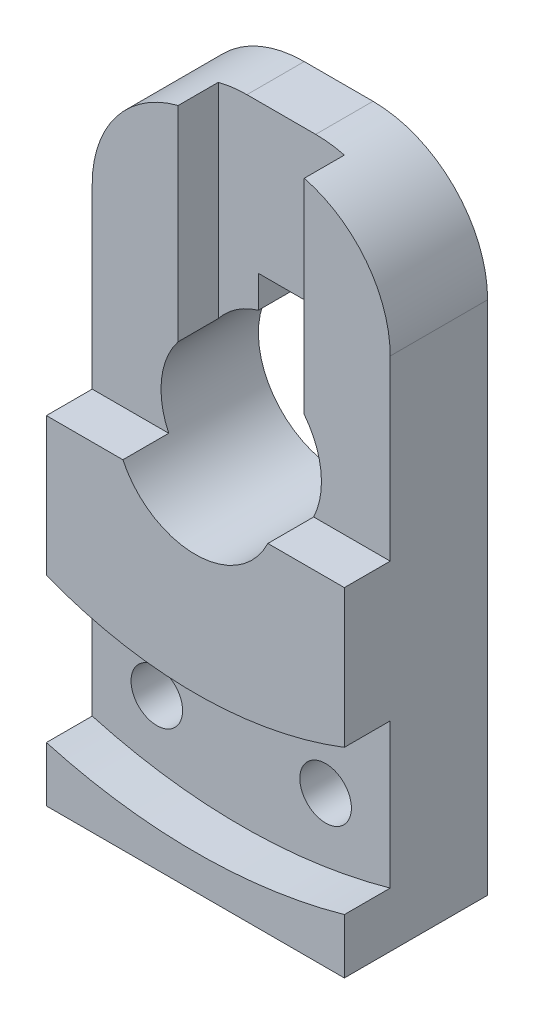
SolidWorks part; units mm, degrees
ref_plane "Front Plane" through (0, 0, 0) normal (1, 0, 0) x (0, 1, 0)
ref_plane "Top Plane" through (0, 0, 0) normal (0, 0, 1) x (0, 1, 0)
ref_plane "Right Plane" through (0, 0, 0) normal (0, 1, 0) x (-1, 0, 0)
sketch "Sketch1" plane through (0, 0, 0) normal (0, 0, 1) x (0, 1, 0)
  line L0 (0, 0) -> (0, 26)
  line L1 (0, 26) -> (90, 26)
  line L2 (110, 6) -> (110, -6)
  line L3 (90, -26) -> (0, -26)
  line L4 (0, -26) -> (0, 26)
  line L5 (110, 0) -> (102, 0) construction
  line L6 (78.4164, 4) -> (84, 4)
  line L8 (78.4164, -4) -> (84, -4)
  line L9 (84, 4) -> (84, -4)
  line L10 (102, 0) -> (17, 0) construction
  arc A0 (90, 26) -> (110, 6) centre (90, 6) cw
  arc A1 (110, -6) -> (90, -26) centre (90, -6) cw
  arc A2 (78.4164, 4) -> (78.4164, -4) centre (65, 0) ccw
  circle A3 centre (18.2858, 14.7289) radius 4.5
  circle A4 centre (18.2858, -14.7289) radius 4.5
  circle A5 centre (102, 0) radius 85 construction
  point P11 (18.9346, 16.2101)
  point P21 (16.92, 13.8192)
  point P23 (0, 0)
  point P24 (0, 0)
  point P25 (84, 0)
  dimension "D2" = 9
  dimension "D6" = 14
  dimension "D8" = 20
  dimension "D1" = 110
  dimension "D3" = 35
  dimension "D4" = 19
  dimension "D5" = 8
  dimension "D7" = 45
  dimension "D9" = 8
  dimension "D10" = 52
  dimension "D11" = 85
extrude "Boss-Extrude1" add sketch "Sketch1" along normal mid plane 25 contours A1 L2 A0 L1 L0 L4 L3 A4 A3 A2 L6 L9 L8
sketch "Sketch2" plane through (0, 110, 0) normal (0, 1, 0) x (-1, 0, 0)
  line L0 (-26, 12.5) -> (-26, 4.5)
  line L1 (-26, 12.5) -> (-26, -12.5) construction
  line L2 (-26, 4.5) -> (-11, 4.5)
  line L3 (-11, 4.5) -> (-11, -2.5)
  line L4 (-11, -2.5) -> (11, -2.5)
  line L5 (0, -2.5) -> (0, 12.5) construction
  line L6 (6, 12.5) -> (-6, 12.5) construction
  line L7 (26, 12.5) -> (-26, 12.5)
  line L8 (11, 4.5) -> (11, -2.5)
  line L9 (26, 4.5) -> (11, 4.5)
  line L10 (26, 12.5) -> (26, 4.5)
  dimension "D1" = 7
  dimension "D2" = 8
  dimension "D3" = 22
extrude "Cut-Extrude1" cut sketch "Sketch2" against normal blind 51 and the other way through all
sketch "Sketch3" plane through (0, 0, 12.5) normal (0, 0, 1) x (1, 0, 0)
  line L1 (-26, 0) -> (-26, 90) construction
  line L3 (26, 90) -> (26, 0) construction
  line L4 (-26, 9.5879) -> (-26, 34.8584)
  line L5 (26, 9.5879) -> (26, 34.8584)
  arc A2 (-26, 9.5879) -> (26, 9.5879) centre (0, 102) ccw
  arc A3 (-26, 34.8584) -> (26, 34.8584) centre (0, 102) ccw
  dimension "D1" = 96
  dimension "D2" = 72
extrude "Cut-Extrude2" cut sketch "Sketch3" against normal blind 8
